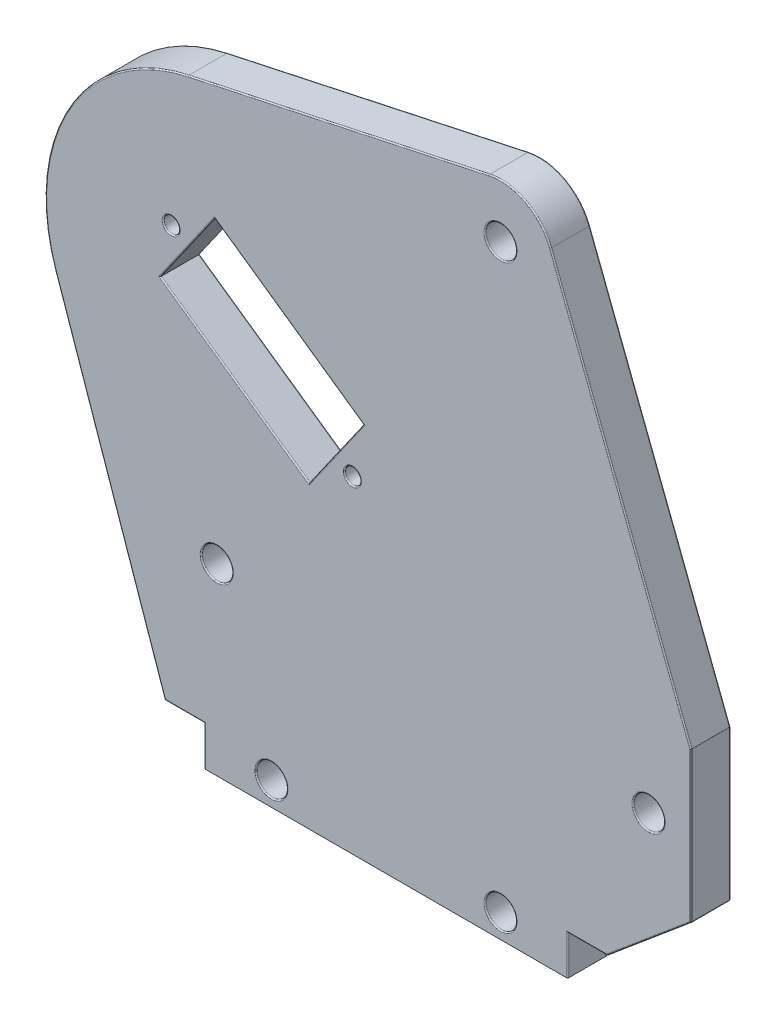
SolidWorks part; units mm, degrees
ref_plane "Front Plane" through (0, 0, 0) normal (0, 0, 1) x (1, 0, 0)
ref_plane "Top Plane" through (0, 0, 0) normal (0, 1, 0) x (1, 0, 0)
ref_plane "Right Plane" through (0, 0, 0) normal (1, 0, 0) x (0, 0, -1)
sketch "Sketch1" plane through (0, 0, 0) normal (0, 0, 1) x (1, 0, 0)
  line L0 (-23, 0) -> (23, 0) construction
  line L1 (-23, 0) -> (23, 0)
  line L2 (23, 0) -> (23, 10) construction
  line L3 (23, 10) -> (28, 10) construction
  line L4 (23, 0) -> (23, 10)
  line L5 (23, 10) -> (28, 10)
  line L6 (28, 10) -> (38.6097, 18.9026) construction
  line L7 (38.6097, 18.9026) -> (38.6097, 37.9026) construction
  line L8 (38.6097, 37.9026) -> (20.8343, 83.9454) construction
  line L9 (-25.0297, 79.9436) -> (13.0723, 88.1382) construction
  line L10 (-28, 10) -> (-41.8438, 50.1182) construction
  line L11 (-23, 10) -> (-28, 10) construction
  line L12 (-23, 0) -> (-23, 10) construction
  line L13 (28, 10) -> (38.6097, 18.9026)
  line L14 (38.6097, 18.9026) -> (38.6097, 37.9026)
  line L15 (38.6097, 37.9026) -> (20.8343, 83.9454)
  line L16 (-25.0297, 79.9436) -> (13.0723, 88.1382)
  line L17 (-28, 10) -> (-41.8438, 50.1182)
  line L18 (-23, 10) -> (-28, 10)
  line L19 (-23, 0) -> (-23, 10)
  line L20 (0, 0) -> (0, 10) construction
  line L21 (-21.6935, 65.9364) -> (-28.5764, 56.1065)
  line L22 (-21.6935, 65.9364) -> (-2.853, 52.7441)
  line L23 (-28.5764, 56.1065) -> (-9.7359, 42.9143)
  line L24 (-2.853, 52.7441) -> (-9.7359, 42.9143)
  line L25 (-6.2944, 47.8292) -> (-25.1349, 61.0215) construction
  line L26 (-15.7147, 54.4253) -> (-19.1561, 49.5104) construction
  arc A0 (20.8343, 83.9454) -> (13.0723, 88.1382) centre (14.5, 81.5) ccw construction
  arc A1 (-25.0297, 79.9436) -> (-41.8438, 50.1182) centre (-20.22, 57.58) ccw construction
  arc A2 (20.8343, 83.9454) -> (13.0723, 88.1382) centre (14.5, 81.5) ccw
  arc A3 (-25.0297, 79.9436) -> (-41.8438, 50.1182) centre (-20.22, 57.58) ccw
  circle A4 centre (-27.1828, 62.4554) radius 1
  circle A5 centre (-4.2465, 46.3953) radius 1
  point P14 (-14.5, 8)
  point P15 (14.5, 8)
  point P16 (33.3597, 28.4026)
  point P17 (-21.5, 28.4026)
  point P18 (38.6097, 28.4026)
  point P19 (14.5, 81.5)
  point P24 (-20.22, 57.58)
  dimension "D9" = 2
  dimension "D1" = 5.25
  dimension "D2" = 8
  dimension "D3" = 21.5
  dimension "D4" = 23
  dimension "D5" = 12
  dimension "D6" = 35
  dimension "D7" = 6
  dimension "D8" = 2.5
extrude "Boss-Extrude1" add sketch "Sketch1" along normal blind 5
hole_wizard "M3.5 Clearance Hole1" positions "Sketch3" profile "Sketch2" hole size "M3.5" standard "ISO"
sketch "Sketch3" plane through (0, 0, 5) normal (0, 0, 1) x (1, 0, 0)
  point P0 (14.5, 81.5)
  point P3 (33.2378, 28.2545)
  point P5 (-21.4122, 28.2545)
  point P7 (-14.5, 8)
  point P9 (14.5, 8)
sketch "Sketch2" plane through (14.5, 81.5, 5) normal (1, 0, 0) x (0, -1, 0)
  line L0 (0, 0) -> (0, 11.1717)
  line L1 (0, 11.1717) -> (1.95, 10)
  line L2 (1.95, 10) -> (1.95, 0)
  line L5 (1.95, 0) -> (0, 0)
  line L10 (0, 11.1717) -> (-1.95, 10) construction
  line L11 (0, -6.35) -> (0, 107.95) construction
  dimension "Hole Dia." = 3.9
  dimension "Hole Depth" = 10
  dimension "Drill Angle" = 118
fillet "Fillet1" radius 0.15 52 edges at (16.45, 81.5, 5) (16.45, 81.5, 0) (35.1878, 28.2545, 5) (35.1878, 28.2545, 0) (-19.4622, 28.2545, 5) (-19.4622, 28.2545, 0) (-12.55, 8, 5) (-12.55, 8, 0) (16.45, 8, 5) (16.45, 8, 0) (-5.2465, 46.3953, 0) (-5.2465, 46.3953, 5) (-26.1828, 62.4554, 0) (-26.1828, 62.4554, 5) (-12.2732, 59.3402, 0) (-25.1349, 61.0215, 0) (-19.1561, 49.5104, 0) (-6.2944, 47.8292, 0) (-12.2732, 59.3402, 5) (-25.1349, 61.0215, 5) (-19.1561, 49.5104, 5) (-6.2944, 47.8292, 5) (-23, 5, 0) (0, 0, 0) (23, 5, 0) (25.5, 10, 0) (33.3049, 14.4513, 0) (38.6097, 28.4026, 0) (29.722, 60.924, 0) (17.727, 87.4741, 0) (-5.9787, 84.0409, 0) (-40.1467, 68.8136, 0) (-34.9219, 30.0591, 0) (-25.5, 10, 0) (-23, 5, 5) (0, 0, 5) (23, 5, 5) (25.5, 10, 5) (33.3049, 14.4513, 5) (38.6097, 28.4026, 5) (29.722, 60.924, 5) (17.727, 87.4741, 5) (-5.9787, 84.0409, 5) (-40.1467, 68.8136, 5) (-34.9219, 30.0591, 5) (-25.5, 10, 5) (-28, 10, 2.5) (38.6097, 37.9026, 2.5) (38.6097, 18.9026, 2.5) (28, 10, 2.5) (-23, 0, 2.5) (23, 0, 2.5)
sketch "Sketch4" plane through (0, 0, 5) normal (0, 0, 1) x (1, 0, 0)
  line L0 (-23, 0.15) -> (-23, 10) construction
  line L1 (-23, 5) -> (23, 5)
  line L2 (-23, 5) -> (-23, 0)
  line L3 (-23, 0) -> (23, 0)
  line L4 (23, 5) -> (23, 0)
  line L5 (22.85, 0) -> (-22.85, 0) construction
  line L6 (23, 10) -> (23, 0.15) construction
  dimension "D1" = 5
extrude "Cut-Extrude4" cut sketch "Sketch4" against normal blind 10
